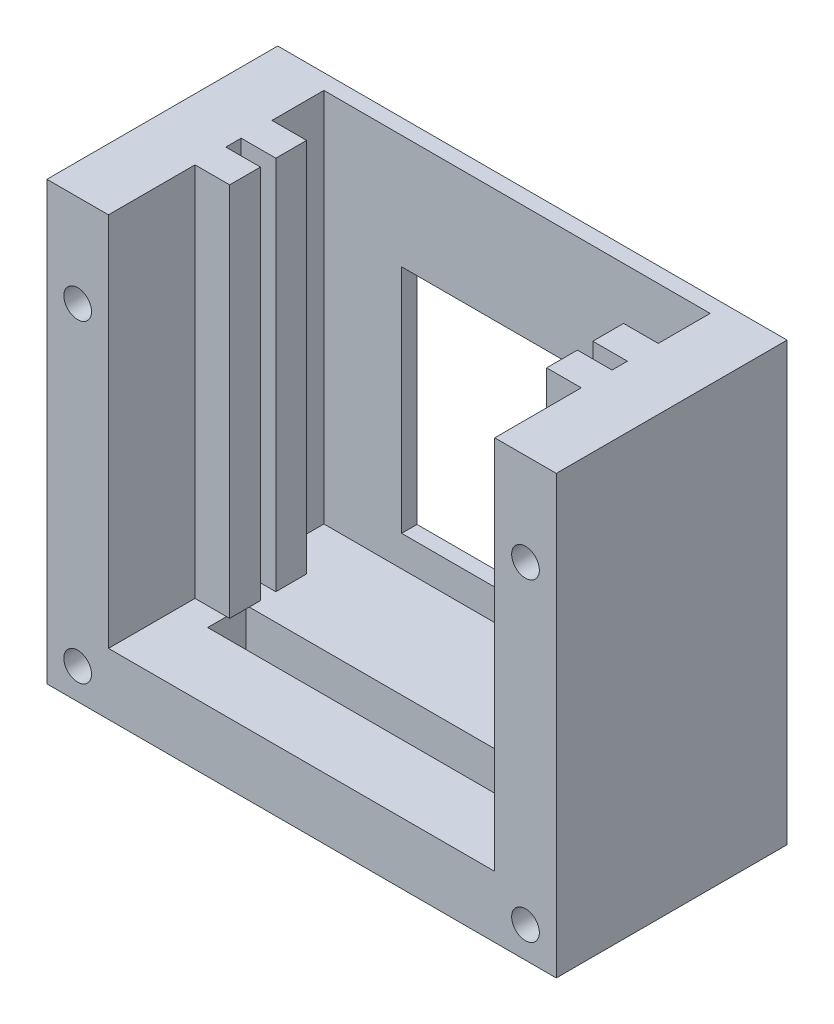
SolidWorks part; units mm, degrees
ref_plane "Plan de face" through (0, 0, 0) normal (0, 0, 1) x (1, 0, 0)
ref_plane "Plan de dessus" through (0, 0, 0) normal (0, 1, 0) x (1, 0, 0)
ref_plane "Plan de droite" through (0, 0, 0) normal (1, 0, 0) x (0, 0, -1)
sketch "Esquisse1" plane through (0, 0, 0) normal (0, 0, 1) x (1, 0, 0)
  line L0 (0, 0) -> (0, -27) construction
  line L1 (0, -27) -> (0, 30) construction
  line L2 (0, 0) -> (25.4165, -15.9375) construction
  line L3 (25.4165, -15.9375) -> (-22.8748, 14.3437) construction
  line L4 (-25.4165, -15.9375) -> (0, 0) construction
  line L5 (0, 0) -> (22.8748, 14.3437) construction
  line L6 (0, 30) -> (25.4165, -15.9375) construction
  line L8 (12.5, -14) -> (-12.5, -14)
  line L9 (12.5, -14) -> (12.5, -17)
  line L10 (12.5, -17) -> (-12.5, -17)
  line L11 (-12.5, -14) -> (-12.5, -17)
  circle A0 centre (0, 0) radius 37
  circle A1 centre (0, 30) radius 1.5
  circle A2 centre (-22.8748, 14.3437) radius 1.5
  circle A3 centre (-25.4165, -15.9375) radius 1.5
  circle A4 centre (0, -27) radius 1.5
  circle A5 centre (25.4165, -15.9375) radius 1.5
  circle A6 centre (22.8748, 14.3437) radius 1.5
  dimension "D1" = 74
  dimension "D11" = 3
  dimension "D12" = 3
  dimension "D13" = 3
  dimension "D14" = 3
  dimension "D15" = 3
  dimension "D16" = 3
  dimension "D2" = 27
  dimension "D3" = 57
  dimension "D4" = 57
  dimension "D5" = 30
  dimension "D6" = 30
  dimension "D7" = 27
  dimension "D8" = 52.5
  dimension "D9" = 52.5
  dimension "D10" = 47.25
  dimension "D17" = 25
  dimension "D18" = 3
  dimension "D19" = 10
  dimension "D20" = 12.5
extrude "Boss.-Extru.1" add sketch "Esquisse1" along normal blind 2
sketch "Esquisse2" plane through (0, 0, 0) normal (0, 0, -1) x (-1, 0, 0)
  line L0 (-16.55, 14.9) -> (-16.55, -13.5)
  line L1 (-12.55, 14.9) -> (12.55, 14.9)
  line L2 (-12.55, 14.9) -> (-12.55, -9.5)
  line L3 (-12.55, -9.5) -> (12.55, -9.5)
  line L4 (12.55, 14.9) -> (12.55, -9.5)
  line L5 (-16.55, -13.5) -> (16.55, -13.5)
  line L6 (16.55, -13.5) -> (16.55, 14.9)
  line L7 (16.55, 14.9) -> (12.55, 14.9)
  line L8 (-16.55, 14.9) -> (-12.55, 14.9)
  point P0 (0, 0)
  dimension "D1" = 25.1
  dimension "D2" = 9.5
  dimension "D3" = 24.4
  dimension "D4" = 4
  dimension "D5" = 4
  dimension "D6" = 4
  dimension "D7" = 12.55
extrude "Boss.-Extru.2" add sketch "Esquisse2" along normal blind 15 contours L8 L0 L5 L6 L7 L4 L3 L2
sketch "Esquisse3" plane through (-12.55, 0, 0) normal (1, 0, 0) x (0, 0, -1)
  line L0 (15, 14.9) -> (0, 14.9) construction
  line L1 (10.625, 14.9) -> (8.625, 14.9)
  line L2 (10.625, 14.9) -> (10.625, -13.5)
  line L3 (10.625, -13.5) -> (8.625, -13.5)
  line L4 (8.625, 14.9) -> (8.625, -13.5)
  line L5 (15, -13.5) -> (0, -13.5) construction
  line L6 (0, 14.9) -> (7.5, 14.9) construction
  line L8 (5.625, 14.9) -> (7.625, 14.9)
  line L9 (5.625, 14.9) -> (5.625, -13.5)
  line L10 (5.625, -13.5) -> (7.625, -13.5)
  line L11 (7.625, 14.9) -> (7.625, -13.5)
  line L12 (8, 14.9) -> (8, -13.5) construction
  dimension "D1" = 2
  dimension "D2" = 0.625
  dimension "D3" = 2
  dimension "D4" = 1
  dimension "D5" = 0.375
  dimension "D6" = 0.5
extrude "Boss.-Extru.3" add sketch "Esquisse3" along normal blind 2.25 contours L11 L10 L9 L8 | L2 L3 L4 L1
sketch "Esquisse5" plane through (12.55, 0, 0) normal (-1, 0, 0) x (0, 0, 1)
  line L1 (-10.625, 14.9) -> (-8.625, 14.9)
  line L2 (-10.625, 14.9) -> (-10.625, -9.5)
  line L3 (-10.625, -9.5) -> (-8.625, -9.5)
  line L4 (-8.625, 14.9) -> (-8.625, -9.5)
  line L5 (-7.625, 14.9) -> (-5.625, 14.9)
  line L6 (-7.625, 14.9) -> (-7.625, -9.5)
  line L7 (-7.625, -9.5) -> (-5.625, -9.5)
  line L8 (-5.625, 14.9) -> (-5.625, -9.5)
extrude "Boss.-Extru.4" add sketch "Esquisse5" along normal blind 2.25
sketch "Esquisse7" plane through (0, 0, -15) normal (0, 0, -1) x (-1, 0, 0)
  line L1 (-16.55, 14.9) -> (16.55, 14.9)
  line L2 (-16.55, 14.9) -> (-16.55, -13.5)
  line L3 (-16.55, -13.5) -> (16.55, -13.5)
  line L4 (16.55, 14.9) -> (16.55, -13.5)
extrude "Boss.-Extru.5" add sketch "Esquisse7" against normal blind 1
sketch "Esquisse8" plane through (0, 0, -15) normal (0, 0, -1) x (-1, 0, 0)
  line L1 (-7.5, 7.5) -> (7.5, 7.5)
  line L2 (-7.5, 7.5) -> (-7.5, -7.5)
  line L3 (-7.5, -7.5) -> (7.5, -7.5)
  line L4 (7.5, 7.5) -> (7.5, -7.5)
  line L5 (-7.5, 7.5) -> (7.5, -7.5) construction
  line L6 (-7.5, -7.5) -> (7.5, 7.5) construction
  point P0 (0, 0)
  dimension "D1" = 15
  dimension "D2" = 15
extrude "Enlèv. mat.-Extru.1" cut sketch "Esquisse8" against normal blind 3 contours L3 L4 L1 L2
sketch "Esquisse9" plane through (0, -13.5, 0) normal (0, -1, 0) x (1, 0, 0)
  line L0 (16.55, 0) -> (-16.55, 0) construction
  line L1 (-10.5, -4.4) -> (10.5, -4.4)
  line L2 (-10.5, -4.4) -> (-10.5, -6.9)
  line L3 (-10.5, -6.9) -> (10.5, -6.9)
  line L4 (10.5, -4.4) -> (10.5, -6.9)
  line L6 (10.5, -4.4) -> (10.5, 0) construction
  line L7 (10.5, 0) -> (-10.5, 0) construction
  line L8 (-10.5, 0) -> (-10.5, -4.4) construction
  point P6 (0, -4.4)
  dimension "D1" = 21
  dimension "D2" = 2.5
  dimension "D3" = 4.4
  dimension "D4" = 0
extrude "Enlèv. mat.-Extru.2" cut sketch "Esquisse9" against normal up to surface (4 mm away) contours L1 L4 L3 L2 up to face at (0, -9.5, -7.9)
sketch "Esquisse10" plane through (0, 0, 2) normal (0, 0, 1) x (1, 0, 0)
  line L0 (16.55, -13.5) -> (-16.55, -13.5) construction
  line L1 (-16.55, -13.5) -> (-16.55, 14.9) construction
  line L2 (16.55, 14.9) -> (16.55, -13.5) construction
  line L3 (16.55, 14.9) -> (12.55, 14.9) construction
  line L4 (-16.55, 14.9) -> (-12.55, 14.9) construction
  circle A0 centre (-14.55, 8.9) radius 0.9
  circle A1 centre (-14.55, -11.5) radius 0.9
  circle A2 centre (14.55, -11.5) radius 0.9
  circle A3 centre (14.55, 8.9) radius 0.9
  dimension "D1" = 1.8
  dimension "D2" = 1.8
  dimension "D3" = 1.8
  dimension "D4" = 1.8
  dimension "D5" = 2
  dimension "D6" = 2
  dimension "D7" = 2
  dimension "D8" = 2
  dimension "D9" = 2
  dimension "D10" = 6
  dimension "D11" = 6
  dimension "D12" = 2
extrude "Enlèv. mat.-Extru.3" cut sketch "Esquisse10" against normal blind 19
sketch "Esquisse11" plane through (0, 0, 2) normal (0, 0, 1) x (1, 0, 0)
  circle A0 centre (0, 0) radius 37
extrude "Enlèv. mat.-Extru.4" cut sketch "Esquisse11" against normal blind 2
sketch "Sketch1" plane through (0, 0, -15) normal (0, 0, -1) x (-1, 0, 0)
  line L0 (7.5, 7.5) -> (-7.5, -7.5)
  line L1 (-7.5, -7.5) -> (-7.5, 7.5)
  line L2 (-7.5, 7.5) -> (7.5, -7.5)
  point P4 (0, 0)
